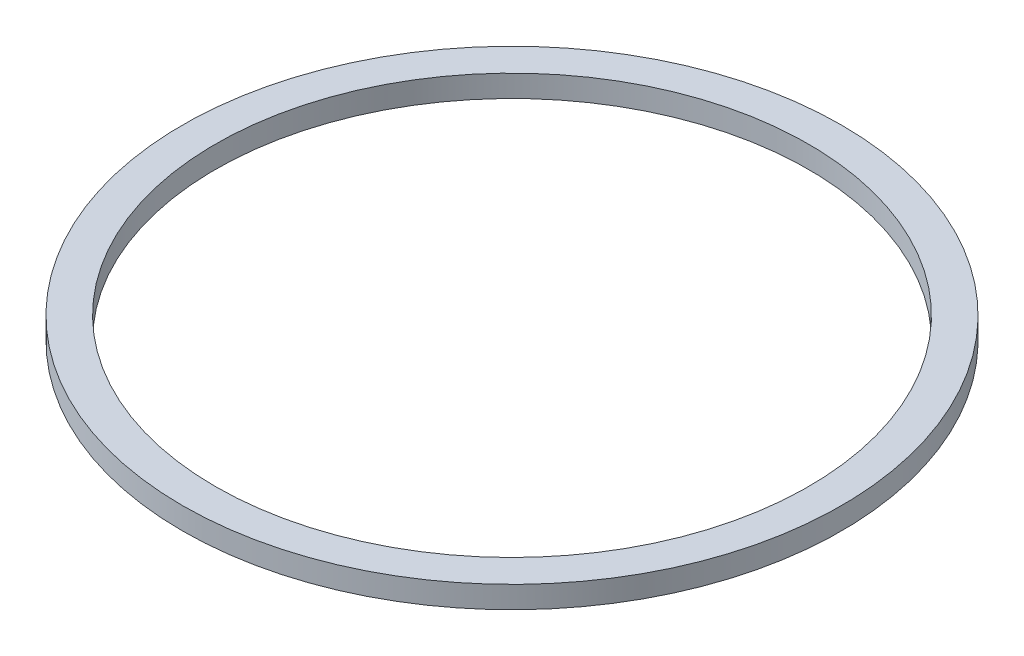
SolidWorks part; units mm, degrees
ref_plane "Plan de face" through (0, 0, 0) normal (0, 0, 1) x (1, 0, 0)
ref_plane "Plan de dessus" through (0, 0, 0) normal (0, 1, 0) x (1, 0, 0)
ref_plane "Plan de droite" through (0, 0, 0) normal (1, 0, 0) x (0, 0, -1)
sketch "Esquisse1" plane through (0, 0, 0) normal (0, 1, 0) x (1, 0, 0)
  circle A0 centre (0, 0) radius 15
  circle A1 centre (0, 0) radius 13.5
  dimension "D1" = 30
  dimension "D2" = 27
extrude "Boss.-Extru.1" add sketch "Esquisse1" along normal blind 1
